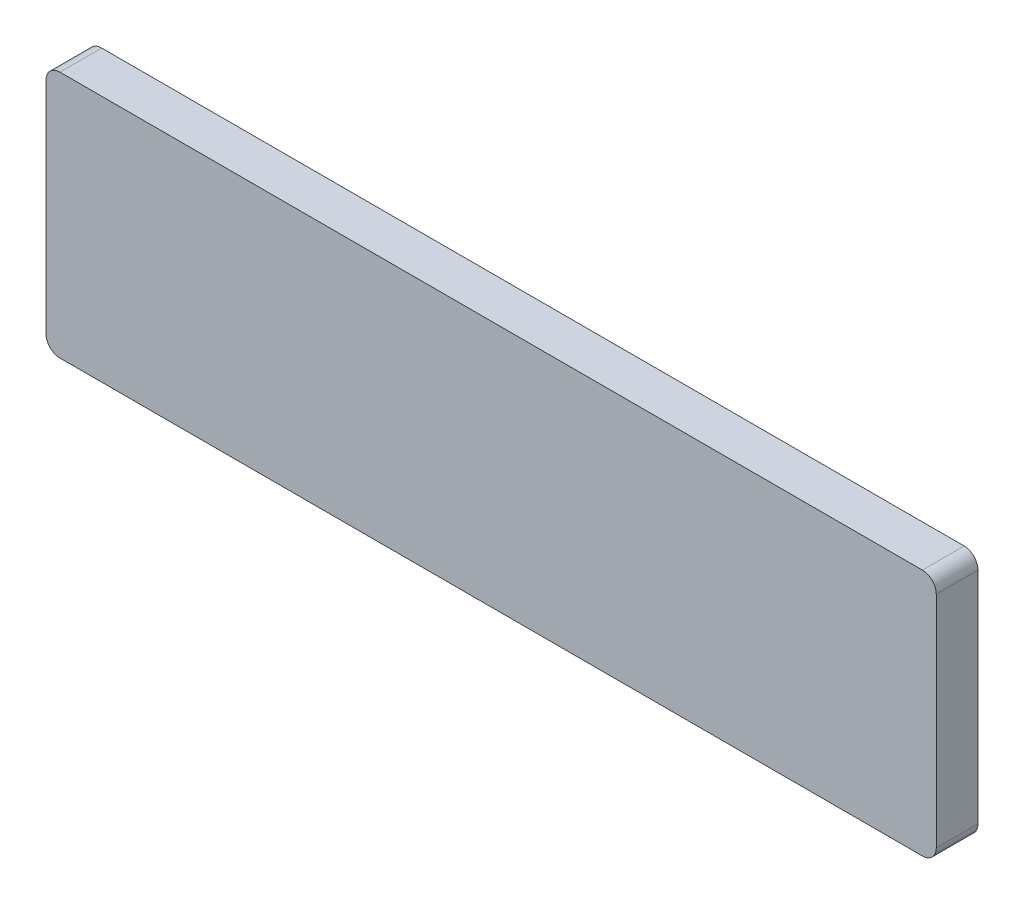
SolidWorks part; units mm, degrees
material "Cedar"
ref_plane "Plan de face" through (0, 0, 0) normal (0, 0, 1) x (1, 0, 0)
ref_plane "Plan de dessus" through (0, 0, 0) normal (0, 1, 0) x (1, 0, 0)
ref_plane "Plan de droite" through (0, 0, 0) normal (1, 0, 0) x (0, 0, -1)
sketch "Sketch1" plane through (0, 0, 0) normal (0, 0, 1) x (1, 0, 0)
  line L1 (-155, 44.5) -> (155, 44.5)
  line L2 (-160, 39.5) -> (-160, -39.5)
  line L3 (-155, -44.5) -> (155, -44.5)
  line L4 (160, 39.5) -> (160, -39.5)
  line L5 (-160, 44.5) -> (160, -44.5) construction
  line L6 (-160, -44.5) -> (160, 44.5) construction
  arc A0 (155, 44.5) -> (160, 39.5) centre (155, 39.5) cw
  arc A1 (155, -44.5) -> (160, -39.5) centre (155, -39.5) ccw
  arc A2 (-160, -39.5) -> (-155, -44.5) centre (-155, -39.5) ccw
  arc A3 (-155, 44.5) -> (-160, 39.5) centre (-155, 39.5) ccw
  point P0 (0, 0)
  dimension "D3" = 5
  dimension "D1" = 320
  dimension "D2" = 89
extrude "Boss-Extrude1" add sketch "Sketch1" along normal mid plane 15
